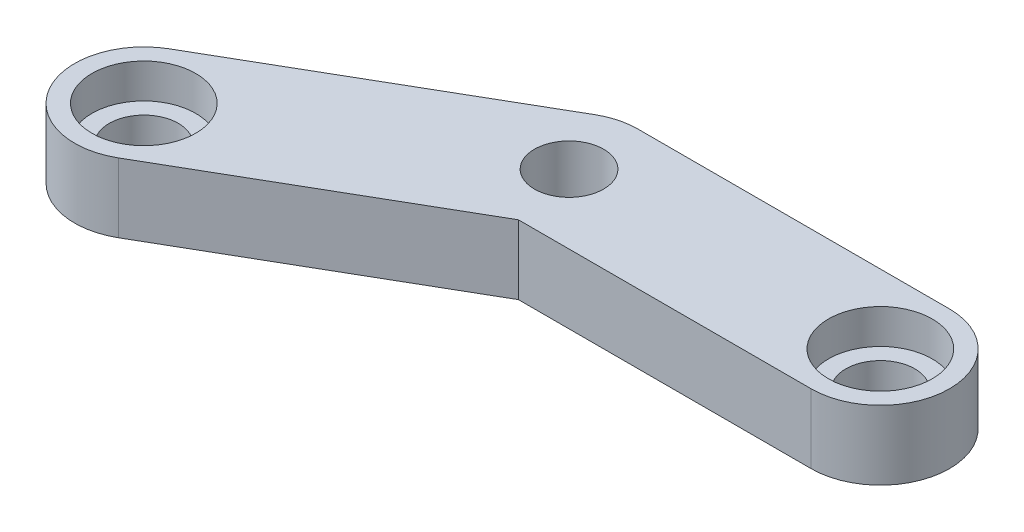
SolidWorks part; units mm, degrees
ref_plane "Front Plane" through (0, 0, 0) normal (0, 0, 1) x (1, 0, 0)
ref_plane "Top Plane" through (0, 0, 0) normal (0, 1, 0) x (1, 0, 0)
ref_plane "Right Plane" through (0, 0, 0) normal (1, 0, 0) x (0, 0, -1)
sketch "Sketch1" plane through (0, 0, 0) normal (0, 1, 0) x (1, 0, 0)
  line L0 (0, 0) -> (22.5, 0) construction
  line L1 (0, 5) -> (22.5, 5)
  line L2 (0, -5) -> (22.5, -5)
  arc A0 (0, 5) -> (0, -5) centre (0, 0) ccw
  arc A1 (22.5, -5) -> (22.5, 5) centre (22.5, 0) ccw
  circle A2 centre (0, 0) radius 2.5
  circle A3 centre (22.5, 0) radius 2.5
  point P3 (11.25, 0)
  dimension "D2" = 5
  dimension "D3" = 5
  dimension "D1" = 22.5
extrude "Boss-Extrude1" add sketch "Sketch1" along normal blind 5
sketch "Sketch2" plane through (0, 5, 0) normal (0, 1, 0) x (1, 0, 0)
  line L0 (0, 0) -> (-19.4856, -11.25) construction
  line L1 (2.5, -4.3301) -> (-16.9856, -15.5801)
  line L2 (-2.5, 4.3301) -> (-21.9856, -6.9199)
  line L3 (0, 0) -> (17.237, 0) construction
  arc A0 (2.5, -4.3301) -> (-2.5, 4.3301) centre (0, 0) ccw
  arc A1 (-21.9856, -6.9199) -> (-16.9856, -15.5801) centre (-19.4856, -11.25) ccw
  arc A2 (0, 5) -> (0, -5) centre (0, 0) ccw construction
  circle A3 centre (-19.4856, -11.25) radius 2.5
  circle A4 centre (0, 0) radius 2.5
  point P3 (-9.7428, -5.625)
  circle M2 centre (0, 0) radius 2.5
  arc M3 (0, 5) -> (0, -5) centre (0, 0) ccw
  line M4 (0, -5) -> (22.5, -5)
  dimension "D2" = 5
  dimension "D3" = 5
  dimension "D4" = 150
  dimension "D1" = 22.5
extrude "Boss-Extrude2" add sketch "Sketch2" against normal blind 5 contours L2 A1 L1 M4 M3 | L1 A0 M3 M4 M2
sketch "Sketch3" plane through (0, 5, 0) normal (0, 1, 0) x (1, 0, 0)
  circle A0 centre (22.5, 0) radius 3.75
  circle A1 centre (-19.4856, -11.25) radius 3.75
  dimension "D1" = 7.5
extrude "Cut-Extrude1" cut sketch "Sketch3" against normal blind 2.5
